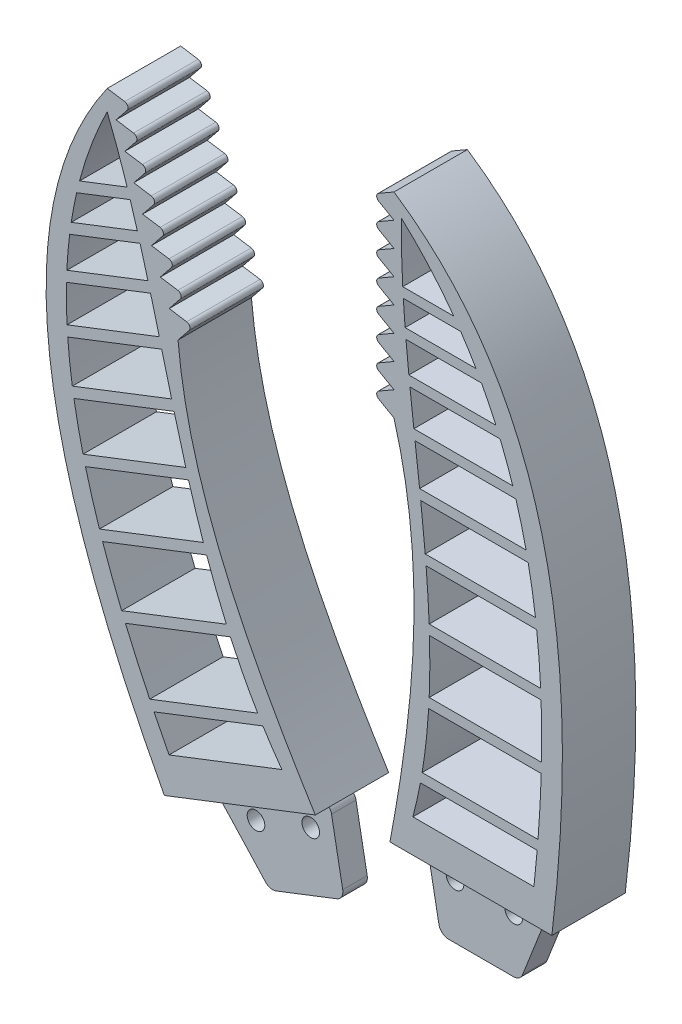
SolidWorks part; units mm, degrees
ref_plane "前视基准面" through (0, 0, 0) normal (0, 0, 1) x (1, 0, 0)
ref_plane "上视基准面" through (0, 0, 0) normal (0, 1, 0) x (1, 0, 0)
ref_plane "右视基准面" through (0, 0, 0) normal (1, 0, 0) x (0, 0, -1)
other "Configuration Table"
sketch "草图2" plane through (0, 0, 0) normal (0, 0, 1) x (1, 0, 0)
  line L0 (1.6604, 0) -> (14.9159, 0)
  line L5 (-0.3054, 1.6321) -> (-2.5923, 13.8521)
  line L6 (16.7779, 1.2699) -> (21.5694, 13.4899)
  line L7 (-0.6265, 16.22) -> (19.7074, 16.22)
  line L8 (2.987, 11.22) -> (14.987, 11.22) construction
  arc A0 (1.6604, 0) -> (-0.3054, 1.6321) centre (1.6604, 2) cw
  arc A1 (14.9159, 0) -> (16.7779, 1.2699) centre (14.9159, 2) ccw
  arc A2 (21.5694, 13.4899) -> (19.7074, 16.22) centre (19.7074, 14.22) ccw
  arc A3 (-2.5923, 13.8521) -> (-0.6265, 16.22) centre (-0.6265, 14.22) cw
  circle A4 centre (2.987, 11.22) radius 1.8
  circle A6 centre (14.987, 11.22) radius 1.8
  point P7 (0, 0)
  dimension "D4" = 2
  dimension "D6" = 3.6
  dimension "D10" = 3.6
  dimension "D1" = 111.41
  dimension "D2" = 100.6
  dimension "D3" = 16.22
  dimension "D7" = 5
  dimension "D8" = 5
  dimension "D9" = 12
extrude "凸台-拉伸1" add sketch "草图2" along normal blind 5
ref_plane "基准面1" through (0, 0, -5) normal (0, 0, -1) x (-1, 0, 0)
sketch "草图3" plane through (0, 0, -5) normal (0, 0, -1) x (-1, 0, 0)
  line L0 (0.6265, 16.22) -> (-27.7726, 16.22)
  line L2 (4.4918, 137.7978) -> (4.4918, 131.6636)
  line L3 (5.3189, 16.22) -> (0.6265, 16.22)
  line L4 (4.4918, 131.6636) -> (7.622, 129.8565)
  line L5 (-24.1038, 23.0109) -> (0.6265, 23.0109)
  line L7 (7.622, 128.4708) -> (4.4918, 126.6636)
  line L8 (7.622, 123.4708) -> (4.4918, 121.6636)
  line L9 (4.4918, 126.6636) -> (7.622, 124.8565)
  line L10 (7.622, 118.4708) -> (4.4918, 116.6636)
  line L11 (4.4918, 121.6636) -> (7.622, 119.8565)
  line L12 (7.622, 113.4708) -> (4.4918, 111.6636)
  line L13 (4.4918, 116.6636) -> (7.622, 114.8565)
  line L14 (7.622, 108.4708) -> (4.4918, 106.6636)
  line L15 (4.4918, 111.6636) -> (7.622, 109.8565)
  line L16 (7.622, 103.4708) -> (4.4918, 101.6636)
  line L17 (4.4918, 106.6636) -> (7.622, 104.8565)
  line L18 (7.622, 98.4708) -> (4.4918, 96.6636)
  line L19 (4.4918, 101.6636) -> (7.622, 99.8565)
  line L20 (7.622, 93.4708) -> (4.4918, 91.6636)
  line L21 (4.4918, 96.6636) -> (7.622, 94.8565)
  arc A0 (7.622, 129.8565) -> (7.622, 128.4708) centre (7.222, 129.1636) cw
  arc A1 (7.622, 124.8565) -> (7.622, 123.4708) centre (7.222, 124.1636) cw
  arc A2 (7.622, 119.8565) -> (7.622, 118.4708) centre (7.222, 119.1636) cw
  arc A3 (7.622, 114.8565) -> (7.622, 113.4708) centre (7.222, 114.1636) cw
  arc A4 (7.622, 109.8565) -> (7.622, 108.4708) centre (7.222, 109.1636) cw
  arc A5 (7.622, 104.8565) -> (7.622, 103.4708) centre (7.222, 104.1636) cw
  arc A6 (7.622, 99.8565) -> (7.622, 98.4708) centre (7.222, 99.1636) cw
  arc A7 (7.622, 94.8565) -> (7.622, 93.4708) centre (7.222, 94.1636) cw
  spline S0 degree 3 poles (-27.7726, 16.22) (-32.4932, 55.4675) (-32.4536, 107.0772) (4.4918, 131.6636) knots 0 0 0 0 1 1 1 1
  spline S1 degree 3 poles (4.4918, 91.6636) (-2.5851, 67.2009) (0.7184, 40.72) (5.3189, 16.22) knots 0 0 0 0 1 1 1 1
  spline S2 degree 3 poles (-24.1038, 23.0109) (-28.0907, 59.3727) (-26.469, 100.898) (2.9735, 127.7972) knots 0 0 0 0 1 1 1 1
  spline S3 degree 3 poles (2.9735, 127.7972) (3.4812, 92.7961) (-8.5608, 57.8193) (0.6265, 23.0109) knots 0 0 0 0 1 1 1 1
  point P21 (8.822, 129.1636)
  point P22 (2.9735, 127.7972)
  point P24 (-19.1956, 88.2096)
  point P33 (-20.029, 86.4594)
  point P38 (-25.6963, 49.0387)
  point P43 (-2.2271, 80.0343)
  point P48 (-3.7273, 44.2132)
  point P53 (0.6265, 23.0109)
  point P55 (-2.4271, 81.6172)
  point P58 (-2.6271, 44.1132)
  point P59 (-1.127, 83.6174)
  point P60 (0.6265, 93.4708)
  point P61 (-2.8272, 54.0142)
  point P62 (-19.829, 91.6636)
  dimension "D3" = 0.8
  dimension "D1" = 60
  dimension "D2" = 5
  dimension "D4" = 5
extrude "凸台-拉伸2" add sketch "草图3" against normal blind 15
sketch "草图5" plane through (0, 0, -5) normal (0, 0, -1) x (-1, 0, 0)
  line L26 (-10.3849, 115.7972) -> (3.2974, 115.7972)
  line L27 (-10.3849, 115.7972) -> (-10.3849, 113.7972)
  line L28 (-10.3849, 113.7972) -> (3.2974, 113.7972)
  line L29 (3.2974, 115.7972) -> (3.2974, 113.7972)
  line L30 (-15.299, 108.7972) -> (3.2974, 108.7972)
  line L31 (-15.299, 108.7972) -> (-15.299, 106.7972)
  line L32 (-15.299, 106.7972) -> (3.2974, 106.7972)
  line L33 (3.2974, 108.7972) -> (3.2974, 106.7972)
  line L34 (-19.0497, 100.7972) -> (2.8732, 100.7972)
  line L35 (-19.0497, 100.7972) -> (-19.0497, 98.7972)
  line L36 (-19.0497, 98.7972) -> (2.8732, 98.7972)
  line L37 (2.8732, 100.7972) -> (2.8732, 98.7972)
  line L38 (-21.7533, 91.7972) -> (2.6381, 91.7972)
  line L39 (-21.7533, 91.7972) -> (-21.7533, 89.7972)
  line L40 (-21.7533, 89.7972) -> (2.6381, 89.7972)
  line L41 (2.6381, 91.7972) -> (2.6381, 89.7972)
  line L42 (-24.0584, 81.7972) -> (1.2111, 81.7972)
  line L43 (-24.0584, 81.7972) -> (-24.0584, 79.7972)
  line L44 (-24.0584, 79.7972) -> (1.2111, 79.7972)
  line L45 (1.2111, 81.7972) -> (1.2111, 79.7972)
  line L46 (-24.8467, 70.7972) -> (0.2743, 70.7972)
  line L47 (-24.8467, 70.7972) -> (-24.8467, 68.7972)
  line L48 (-24.8467, 68.7972) -> (0.2743, 68.7972)
  line L49 (0.2743, 70.7972) -> (0.2743, 68.7972)
  line L50 (-27.1505, 58.7972) -> (0, 58.7972)
  line L51 (-27.1505, 58.7972) -> (-27.1505, 56.7972)
  line L52 (-27.1505, 56.7972) -> (0, 56.7972)
  line L53 (0, 58.7972) -> (0, 56.7972)
  line L54 (-27.1505, 45.7972) -> (-0.3627, 45.7972)
  line L55 (-27.1505, 45.7972) -> (-27.1505, 43.7972)
  line L56 (-27.1505, 43.7972) -> (-0.3627, 43.7972)
  line L57 (-0.3627, 45.7972) -> (-0.3627, 43.7972)
  line L58 (-26.6337, 31.7972) -> (0.2743, 31.7972)
  line L59 (-26.6337, 31.7972) -> (-26.6337, 29.7972)
  line L60 (-26.6337, 29.7972) -> (0.2743, 29.7972)
  line L61 (0.2743, 31.7972) -> (0.2743, 29.7972)
  dimension "D1" = 2
  dimension "D2" = 2
  dimension "D3" = 2
  dimension "D4" = 2
  dimension "D5" = 2
  dimension "D6" = 2
  dimension "D7" = 2
  dimension "D8" = 2
  dimension "D9" = 5
  dimension "D10" = 6
  dimension "D11" = 12
  dimension "D12" = 7
  dimension "D13" = 8
  dimension "D14" = 9
  dimension "D15" = 10
  dimension "D16" = 11
  dimension "D17" = 2
  dimension "D18" = 12
extrude "凸台-拉伸5" add sketch "草图5" against normal blind 15
ref_plane "基准面2" through (-9.8294, -1.8395, 0) normal (-0.9829, -0.184, 0) x (0, 0, 1)
mirror "镜向3" about plane through (-9.8294, -1.8395, 0) normal (-0.9829, -0.184, 0) of bodies 113 108
